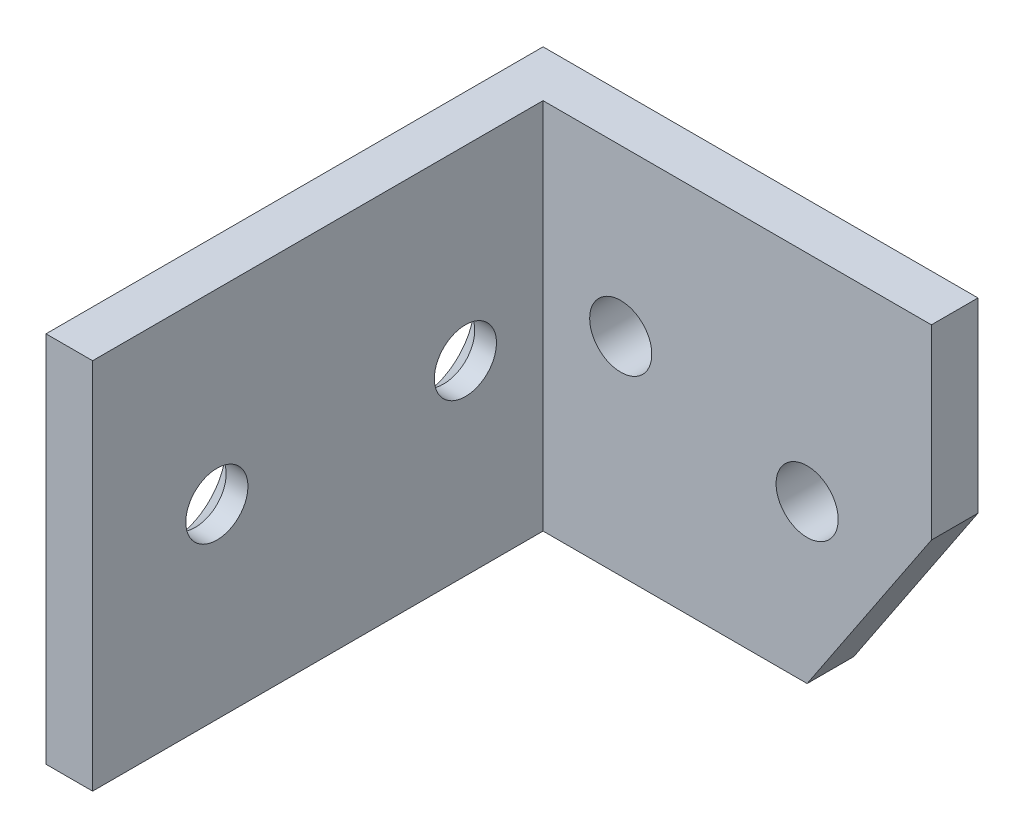
SolidWorks part; units mm, degrees
material "6061 Alloy"
ref_plane "Front Plane" through (0, 0, 0) normal (0, 0, 1) x (1, 0, 0)
ref_plane "Top Plane" through (0, 0, 0) normal (0, 1, 0) x (1, 0, 0)
ref_plane "Right Plane" through (0, 0, 0) normal (1, 0, 0) x (0, 0, -1)
sketch "Sketch1" plane through (0, 0, 0) normal (0, 1, 0) x (1, 0, 0)
  line L0 (0, 0) -> (0, 50.8)
  line L1 (0, 50.8) -> (44.45, 50.8)
  line L2 (4.7625, 0) -> (4.7625, 46.0375)
  line L3 (4.7625, 46.0375) -> (44.45, 46.0375)
  line L4 (0, 0) -> (4.7625, 0)
  line L5 (44.45, 50.8) -> (44.45, 46.0375)
  dimension "D2" = 44.45
  dimension "D3" = 50.8
  dimension "D1" = 4.7625
extrude "Boss-Extrude1" add sketch "Sketch1" along normal blind 38.1
sketch "Sketch2" plane through (0, 0, -50.8) normal (0, 0, -1) x (-1, 0, 0)
  line L0 (0, 24.6103) -> (-44.45, 12.7) construction
  line L1 (0, 38.1) -> (0, 0) construction
  line L2 (-44.45, 38.1) -> (-44.45, 0) construction
  line L3 (-44.45, 0) -> (0, 0) construction
  line L4 (-44.45, 38.1) -> (0, 38.1) construction
  circle A0 centre (-12.7, 21.2074) radius 3.175
  circle A1 centre (-31.75, 16.103) radius 3.175
  dimension "D3" = 6.35
  dimension "D4" = 6.35
  dimension "D5" = 12.7
  dimension "D6" = 19.05
  dimension "D1" = 12.7
  dimension "D2" = 15
extrude "Cut-Extrude1" cut sketch "Sketch2" against normal up to next
sketch "Sketch4" plane through (0, 0, 0) normal (-1, 0, 0) x (0, 0, 1)
  line L0 (0, 38.1) -> (0, 0) construction
  line L1 (-50.8, 38.1) -> (0, 38.1) construction
  circle A0 centre (-12.7, 19.05) radius 3.175
  circle A1 centre (-38.1, 19.05) radius 3.175
  dimension "D1" = 6.35
  dimension "D2" = 6.35
  dimension "D3" = 12.7
  dimension "D4" = 19.05
  dimension "D5" = 19.05
  dimension "D6" = 25.4
extrude "Cut-Extrude2" cut sketch "Sketch4" against normal up to next
chamfer "Chamfer1" distance 2.54 angle 45 2 edges at (0, 19.05, -9.525) (0, 19.05, -34.925)
sketch "Sketch5" plane through (0, 0, -50.8) normal (0, 0, -1) x (-1, 0, 0)
  line L0 (-31.75, 0) -> (-44.45, 19.05)
  line L1 (-44.45, 0) -> (0, 0) construction
  line L2 (-44.45, 38.1) -> (-44.45, 0) construction
  dimension "D1" = 12.7
  dimension "D2" = 19.05
extrude "Cut-Extrude3" cut sketch "Sketch5" against normal through all and the other way through all
